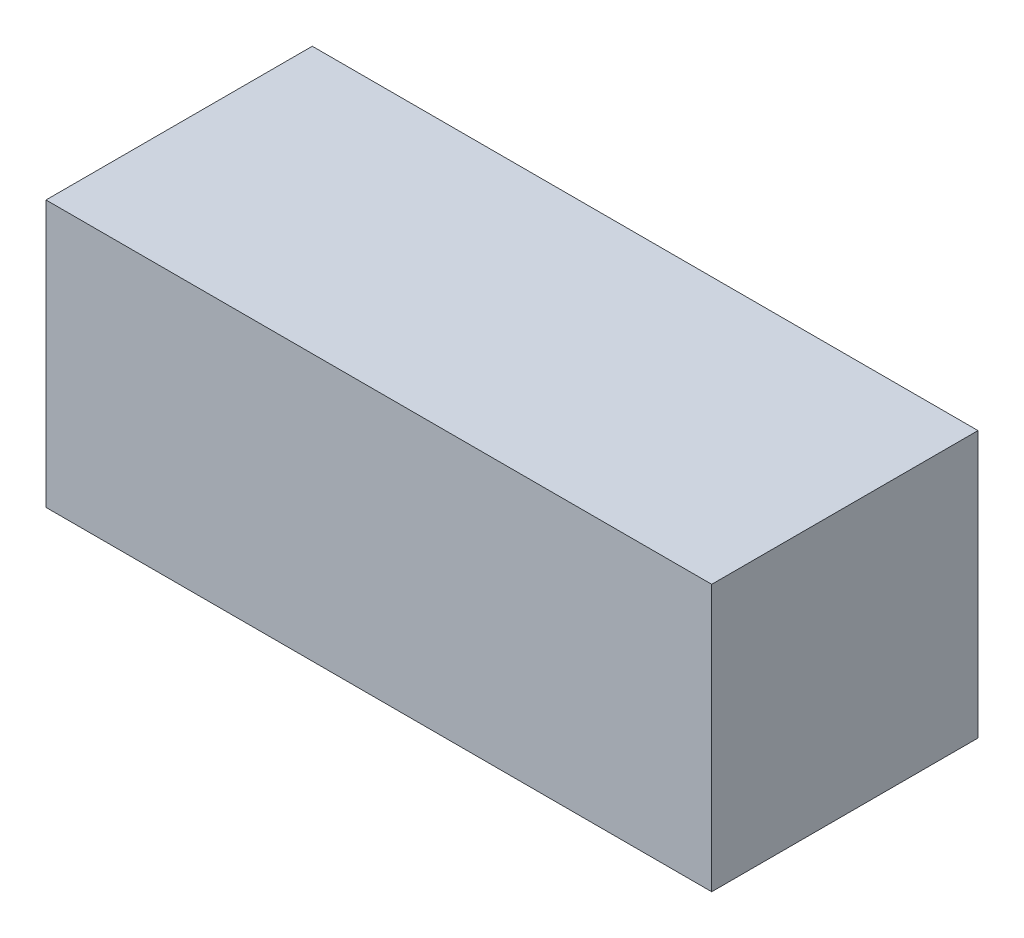
SolidWorks part; units mm, degrees
ref_plane "Front Plane" through (0, 0, 0) normal (0, 0, 1) x (1, 0, 0)
ref_plane "Top Plane" through (0, 0, 0) normal (0, 1, 0) x (1, 0, 0)
ref_plane "Right Plane" through (0, 0, 0) normal (1, 0, 0) x (0, 0, -1)
sketch "Sketch1" plane through (0, 0, 0) normal (1, 0, 0) x (0, 0, -1)
  line L1 (-19.05, -19.05) -> (19.05, -19.05)
  line L2 (-19.05, -19.05) -> (-19.05, 19.05)
  line L3 (-19.05, 19.05) -> (19.05, 19.05)
  line L4 (19.05, -19.05) -> (19.05, 19.05)
  line L5 (-19.05, -19.05) -> (19.05, 19.05) construction
  line L6 (-19.05, 19.05) -> (19.05, -19.05) construction
  point P0 (0, 0)
  dimension "D1" = 38.1
extrude "Boss-Extrude1" add sketch "Sketch1" along normal mid plane 95.25
